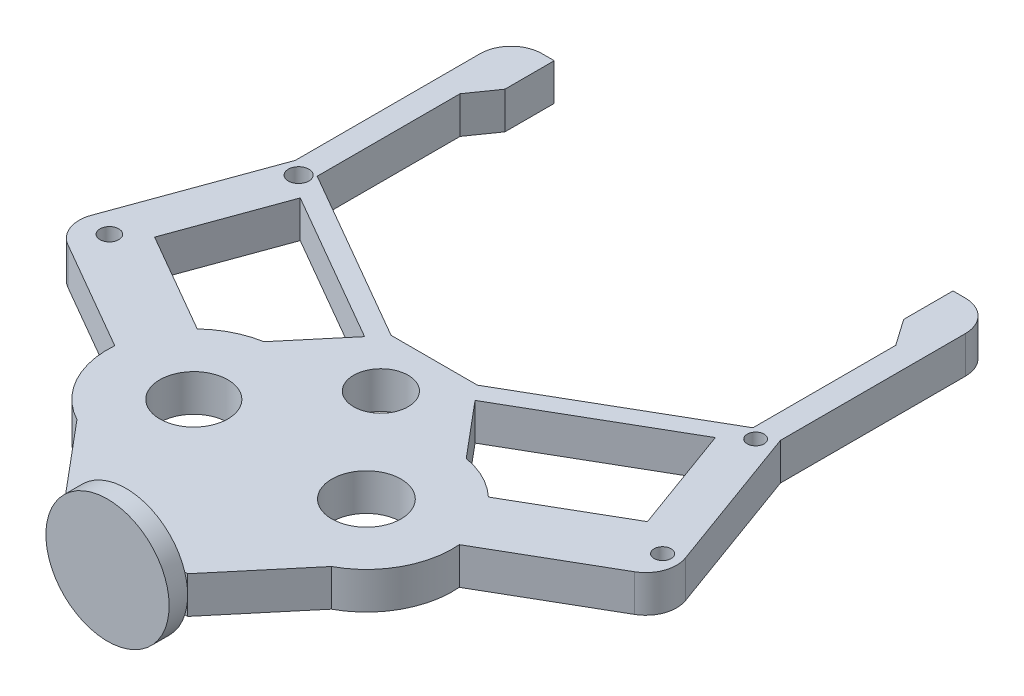
SolidWorks part; units mm, degrees
ref_plane "前视基准面" through (0, 0, 0) normal (0, 0, 1) x (1, 0, 0)
ref_plane "上视基准面" through (0, 0, 0) normal (0, 1, 0) x (1, 0, 0)
ref_plane "右视基准面" through (0, 0, 0) normal (1, 0, 0) x (0, 0, -1)
sketch "草图1" plane through (0, 0, 0) normal (0, 1, 0) x (1, 0, 0)
  line L0 (-10, 0) -> (10, 0)
  line L1 (10, 0) -> (20.6317, 12.6703)
  line L2 (-10, 0) -> (-20.6317, 12.6703)
  line L3 (-7, 50) -> (7, 50)
  line L4 (8.9581, 47.6664) -> (16.4047, 38.7919)
  line L5 (-8.9581, 47.6664) -> (-16.4047, 38.7919)
  line L6 (27.9545, 26.1284) -> (49.6051, 38.6284)
  line L7 (49.6051, 38.6284) -> (39.3445, 66.8192)
  line L8 (39.3445, 66.8192) -> (39.3445, 101.8192)
  line L9 (39.3445, 101.8192) -> (32.3445, 101.8192)
  line L10 (32.3445, 101.8192) -> (32.3445, 93.8192)
  line L11 (32.3445, 93.8192) -> (35.3445, 89.5347)
  line L12 (35.3445, 89.5347) -> (35.3445, 66.3647)
  line L13 (35.3445, 66.3647) -> (7, 50)
  line L14 (23.619, 35.1723) -> (39.9764, 44.6163)
  line L15 (39.9764, 44.6163) -> (33.6728, 61.9354)
  line L16 (33.6728, 61.9354) -> (8.9581, 47.6664)
  line L17 (-7, 50) -> (-35.3445, 66.3647)
  line L18 (-35.3445, 66.3647) -> (-35.3445, 89.5347)
  line L19 (-35.3445, 89.5347) -> (-32.3445, 93.8192)
  line L20 (-32.3445, 93.8192) -> (-32.3445, 101.8192)
  line L21 (-32.3445, 101.8192) -> (-39.3445, 101.8192)
  line L22 (-39.3445, 101.8192) -> (-39.3445, 66.8192)
  line L23 (-39.3445, 66.8192) -> (-49.6051, 38.6284)
  line L24 (-49.6051, 38.6284) -> (-27.9545, 26.1284)
  line L25 (-8.9581, 47.6664) -> (-33.6728, 61.9354)
  line L26 (-33.6728, 61.9354) -> (-39.9764, 44.6163)
  line L27 (-39.9764, 44.6163) -> (-23.619, 35.1723)
  arc A0 (20.6317, 12.6703) -> (27.9545, 26.1284) centre (14, 25) ccw
  arc A1 (-27.9545, 26.1284) -> (-20.6317, 12.6703) centre (-14, 25) ccw
  arc A2 (-16.4047, 38.7919) -> (-23.619, 35.1723) centre (-14, 25) ccw
  arc A3 (23.619, 35.1723) -> (16.4047, 38.7919) centre (14, 25) ccw
  circle A4 centre (-14, 25) radius 5.518
  circle A5 centre (14, 25) radius 5.6119
  circle A6 centre (-44.0443, 41.3501) radius 1.5271
  circle A7 centre (45.7046, 41.3501) radius 1.3826
  circle A8 centre (-37.0051, 65.0094) radius 1.6721
  circle A9 centre (37.146, 65.0094) radius 1.3716
  circle A10 centre (0, 41.3501) radius 4.4285
  dimension "D2" = 28
  dimension "D3" = 28
  dimension "D1" = 25
  dimension "D6" = 10
  dimension "D4" = 50
  dimension "D5" = 50
  dimension "D7" = 6
  dimension "D8" = 20
  dimension "D9" = 30
  dimension "D10" = 30
  dimension "D11" = 25
  dimension "D12" = 30
  dimension "D13" = 50
  dimension "D14" = 7
  dimension "D15" = 100
  dimension "D16" = 100
  dimension "D17" = 3
  dimension "D18" = 3
  dimension "D19" = 50
  dimension "D20" = 3
  dimension "D21" = 4
  dimension "D22" = 7
  dimension "D23" = 8
  dimension "D24" = 35
  dimension "D25" = 35
  dimension "D26" = 7
extrude "凸台-拉伸1" add sketch "草图1" along normal blind 6
sketch "草图2" plane through (0, 0, 0) normal (0, 0, 1) x (1, 0, 0)
  circle A0 centre (0, 3) radius 10
  dimension "D2" = 20
  dimension "D1" = 3
extrude "凸台-拉伸2" add sketch "草图2" along normal blind 3
fillet "圆角1" radius 5 4 edges at (-39.3445, 3, -101.8192) (-49.6051, 3, -38.6284) (49.6051, 3, -38.6284) (39.3445, 3, -101.8192)
